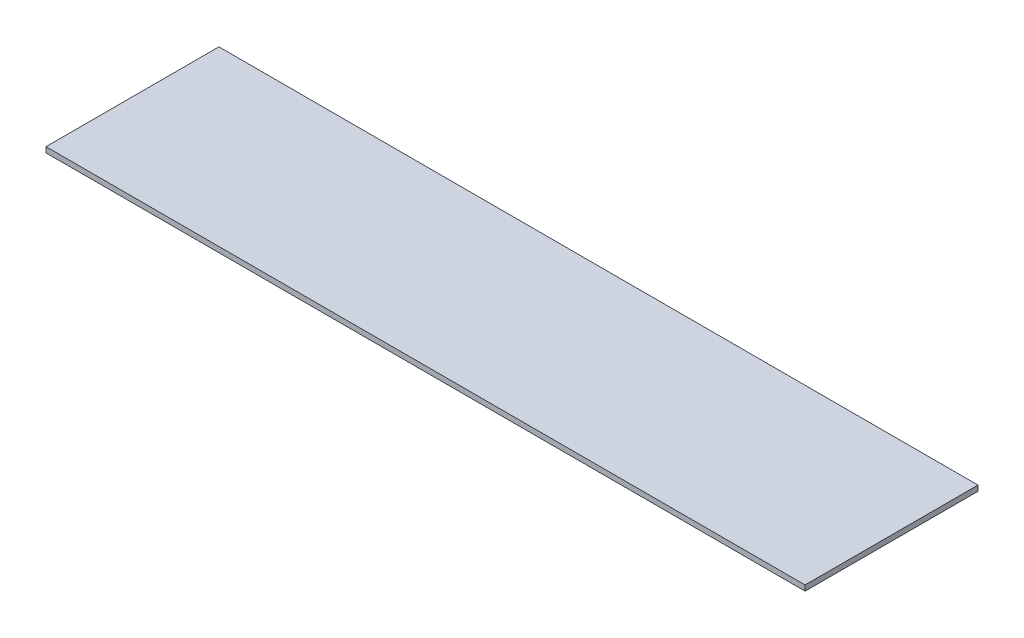
SolidWorks part; units mm, degrees
material "ASTM A36 Steel"
ref_plane "Front Plane" through (0, 0, 0) normal (0, 0, 1) x (1, 0, 0)
ref_plane "Top Plane" through (0, 0, 0) normal (0, 1, 0) x (1, 0, 0)
ref_plane "Right Plane" through (0, 0, 0) normal (1, 0, 0) x (0, 0, -1)
sketch "Sketch1" plane through (0, 0, 0) normal (0, 1, 0) x (1, 0, 0)
  line L0 (0, 101.6) -> (446, 101.6)
  line L2 (0, 0) -> (0, 101.6)
  line L5 (446, 101.6) -> (446, 0)
  line L6 (446, 0) -> (0, 0)
  dimension "D1" = 101.6
  dimension "D2" = 446
extrude "Boss-Extrude1" add sketch "Sketch1" along normal blind 3.175
equation "\"grosor placa\"= ( 1in / 8 )"
equation "\"D1@Boss-Extrude1\"=\"grosor placa\""
equation "\"ancho\"=101.6"
equation "\"D1@Sketch1\"=\"ancho\""
equation "\"Largo\"= 246 + ( 100 * 2 )"
equation "\"D2@Sketch1\"=\"Largo\""
